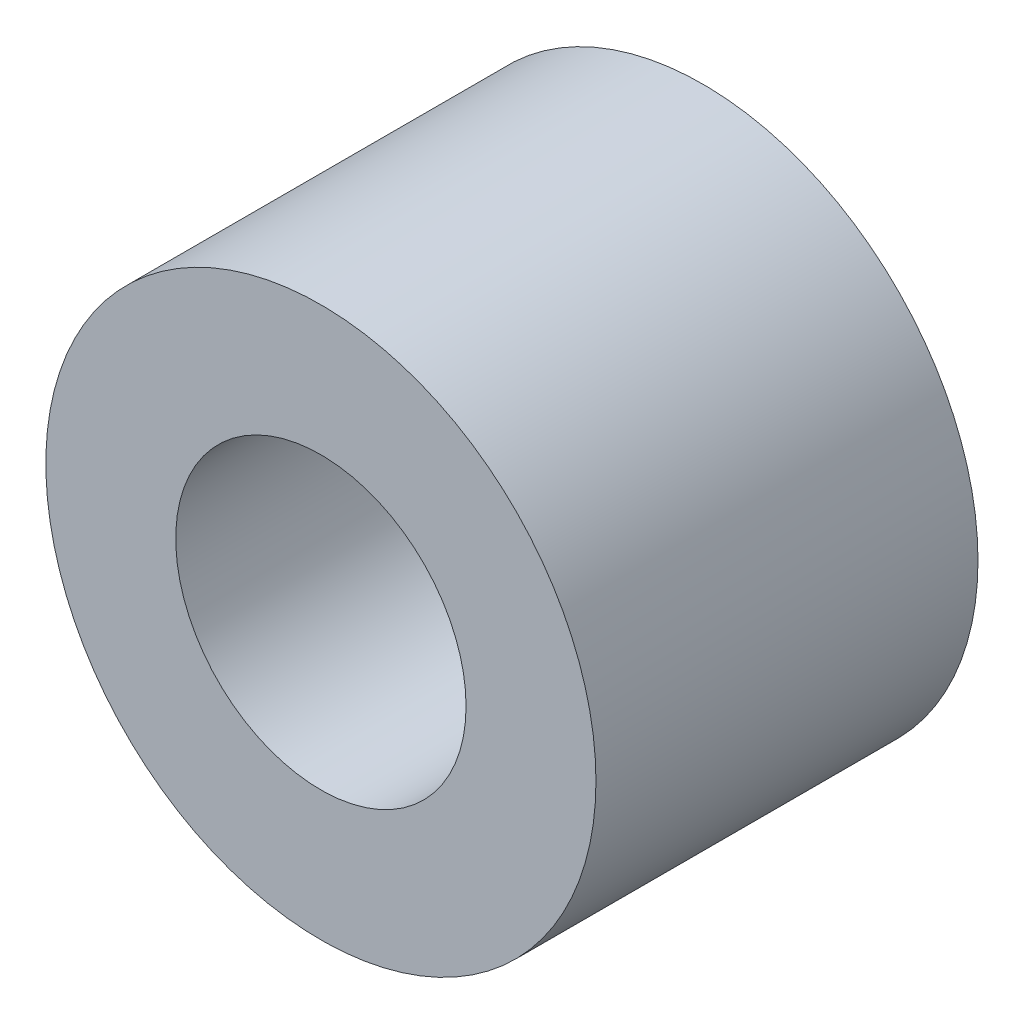
SolidWorks part; units mm, degrees
ref_plane "Front Plane" through (0, 0, 0) normal (0, 0, 1) x (1, 0, 0)
ref_plane "Top Plane" through (0, 0, 0) normal (0, 1, 0) x (1, 0, 0)
ref_plane "Right Plane" through (0, 0, 0) normal (1, 0, 0) x (0, 0, -1)
sketch "Sketch1" plane through (0, 0, 0) normal (0, 0, 1) x (1, 0, 0)
  circle A0 centre (-4.4763, 4.7321) radius 4.572
  circle A1 centre (-4.4763, 4.7321) radius 2.413
extrude "Boss-Extrude1" add sketch "Sketch1" along normal blind 6.35
